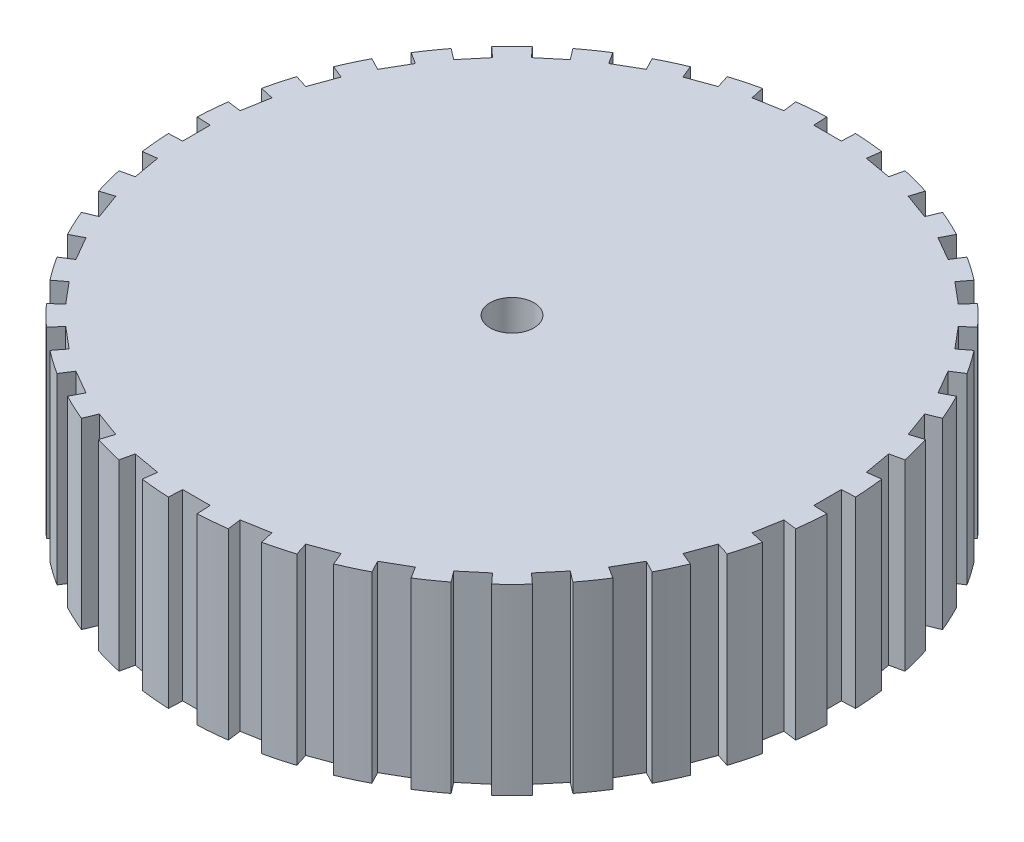
SolidWorks part; units mm, degrees
material "ABS"
ref_plane "Front Plane" through (0, 0, 0) normal (0, 0, 1) x (1, 0, 0)
ref_plane "Top Plane" through (0, 0, 0) normal (0, 1, 0) x (1, 0, 0)
ref_plane "Right Plane" through (0, 0, 0) normal (1, 0, 0) x (0, 0, -1)
sketch "Sketch1" plane through (0, 0, 0) normal (0, 1, 0) x (1, 0, 0)
  line L0 (43.089, -1.8813) -> (43.089, 1.8813)
  line L1 (0, 0) -> (44.8288, 3.922) construction
  line L2 (0, 0) -> (44.8288, -3.922) construction
  line L4 (0, 0) -> (44.8288, 3.922)
  line L5 (44.9572, 1.9629) -> (43.089, 1.8813)
  line L7 (0, 0) -> (44.8288, -3.922)
  line L8 (44.9572, -1.9629) -> (43.089, -1.8813)
  circle A0 centre (0, 0) radius 45 construction
  arc A1 (44.8288, 3.922) -> (44.9572, 1.9629) centre (0, 0) cw
  arc A2 (44.8288, -3.922) -> (44.9572, -1.9629) centre (0, 0) ccw
  point P12 (38.6899, 1.6892)
extrude "Boss-Extrude1" add sketch "Sketch1" along normal blind 25
pattern_circular "CirPattern1" count 36 over 360 about axis through (0, 0, 0) along (0, 1, 0) of "Boss-Extrude1"
sketch "Sketch2" plane through (0, 25, 0) normal (0, 1, 0) x (1, 0, 0)
  circle A0 centre (0, 0) radius 2.99
extrude "Cut-Extrude1" cut sketch "Sketch2" against normal through all
